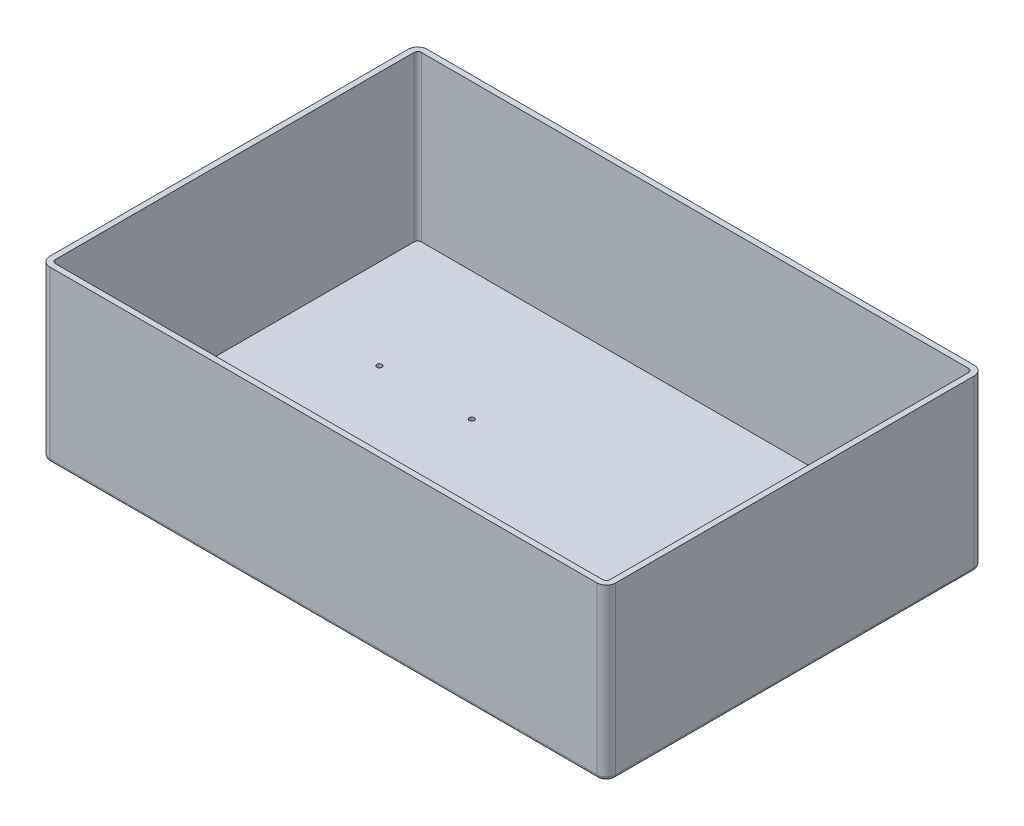
SolidWorks part; units mm, degrees
ref_plane "Front Plane" through (0, 0, 0) normal (0, 0, 1) x (1, 0, 0)
ref_plane "Top Plane" through (0, 0, 0) normal (0, 1, 0) x (1, 0, 0)
ref_plane "Right Plane" through (0, 0, 0) normal (1, 0, 0) x (0, 0, -1)
sketch "Sketch2" plane through (0, 0, 0) normal (0, 1, 0) x (1, 0, 0)
  line L1 (-145, 100) -> (145, 100)
  line L2 (-150, 95) -> (-150, -95)
  line L3 (-145, -100) -> (145, -100)
  line L4 (150, 95) -> (150, -95)
  line L5 (-150, 100) -> (150, -100) construction
  line L6 (-150, -100) -> (150, 100) construction
  arc A0 (-150, -95) -> (-145, -100) centre (-145, -95) ccw
  arc A1 (145, -100) -> (150, -95) centre (145, -95) ccw
  arc A2 (145, 100) -> (150, 95) centre (145, 95) cw
  arc A3 (-145, 100) -> (-150, 95) centre (-145, 95) ccw
  point P0 (0, 0)
  dimension "D3" = 5
  dimension "D1" = 200
  dimension "D2" = 300
extrude "Boss-Extrude1" add sketch "Sketch2" along normal blind 90
shell "Shell1" thickness 3
fillet "Fillet1" radius 2 8 edges at (-148.5355, 0, 98.5355) (-150, 0, 0) (-148.5355, 0, -98.5355) (0, 0, -100) (148.5355, 0, -98.5355) (150, 0, 0) (148.5355, 0, 98.5355) (0, 0, 100)
sketch "Sketch3" plane through (0, 3, 0) normal (0, 1, 0) x (1, 0, 0)
  line L0 (-150, 0) -> (150, 0) construction
  line L1 (-150, 95) -> (-150, -95) construction
  line L2 (150, -95) -> (150, 95) construction
  line L3 (0, 100) -> (0, -100) construction
  line L4 (145, 100) -> (-145, 100) construction
  line L5 (-145, -100) -> (145, -100) construction
  line L6 (0, -100) -> (-148.5355, 98.5355) construction
  line L7 (74.8156, 0) -> (-74.8156, 0) construction
  line L9 (-99.3156, 29) -> (-50.3156, 29) construction
  line L10 (-99.3156, 29) -> (-99.3156, -29) construction
  line L11 (-99.3156, -29) -> (-50.3156, -29) construction
  line L12 (-50.3156, 29) -> (-50.3156, -29) construction
  line L13 (-99.3156, 29) -> (-50.3156, -29) construction
  line L14 (-99.3156, -29) -> (-50.3156, 29) construction
  line L15 (62.5806, 12.235) -> (87.0506, 12.235) construction
  line L16 (62.5806, 12.235) -> (62.5806, -12.235) construction
  line L17 (62.5806, -12.235) -> (87.0506, -12.235) construction
  line L18 (87.0506, 12.235) -> (87.0506, -12.235) construction
  line L19 (62.5806, 12.235) -> (87.0506, -12.235) construction
  line L20 (62.5806, -12.235) -> (87.0506, 12.235) construction
  arc A0 (-145, 100) -> (-150, 95) centre (-145, 95) ccw construction
  circle A2 centre (-99.3156, -29) radius 1.35
  circle A3 centre (-50.3156, -29) radius 1.35
  circle A4 centre (-50.3156, 29) radius 1.35
  circle A5 centre (-99.3156, 29) radius 1.35
  circle A6 centre (87.0506, -12.235) radius 1.35
  circle A7 centre (87.0506, 12.235) radius 1.35
  circle A8 centre (62.5806, 12.235) radius 1.35
  circle A9 centre (62.5806, -12.235) radius 1.35
  point P28 (0, 0)
  dimension "D3" = 2.7
  dimension "D6" = 2.7
  dimension "D1" = 49
  dimension "D2" = 58
  dimension "D4" = 24.47
  dimension "D5" = 24.47
extrude "Cut-Extrude1" cut sketch "Sketch3" against normal blind 3
